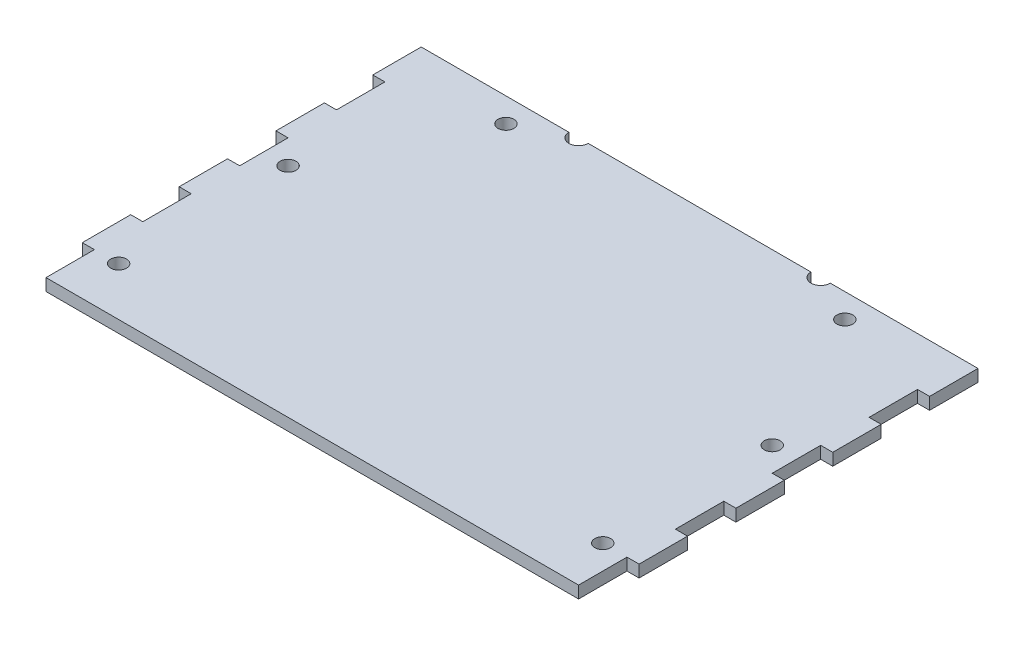
SolidWorks part; units mm, degrees
ref_plane "Front Plane" through (0, 0, 0) normal (0, 0, 1) x (1, 0, 0)
ref_plane "Top Plane" through (0, 0, 0) normal (0, 1, 0) x (1, 0, 0)
ref_plane "Right Plane" through (0, 0, 0) normal (1, 0, 0) x (0, 0, -1)
sketch "Sketch2" plane through (0, 0, 0) normal (0, 1, 0) x (1, 0, 0)
  line L0 (3.175, 0) -> (3.175, 12.7)
  line L1 (3.175, 12.7) -> (0, 12.7)
  line L2 (0, 50.8) -> (0, 38.1)
  line L3 (0, 25.4) -> (3.175, 25.4)
  line L4 (3.175, 38.1) -> (0, 38.1)
  line L5 (0, 76.2) -> (0, 63.5)
  line L6 (0, 50.8) -> (3.175, 50.8)
  line L7 (3.175, 63.5) -> (0, 63.5)
  line L8 (146.05, 101.6) -> (146.05, 88.9)
  line L9 (0, 76.2) -> (3.175, 76.2)
  line L10 (3.175, 25.4) -> (3.175, 38.1)
  line L11 (3.175, 88.9) -> (0, 88.9)
  line L12 (146.05, 25.4) -> (146.05, 12.7)
  line L13 (0, 101.6) -> (3.175, 101.6)
  line L14 (3.175, 50.8) -> (3.175, 63.5)
  line L15 (3.175, 88.9) -> (28.575, 88.9) construction
  line L16 (28.575, 88.9) -> (28.575, 95.25) construction
  line L17 (117.475, 88.9) -> (117.475, 95.25) construction
  line L18 (3.175, 76.2) -> (3.175, 88.9)
  line L19 (9.525, 0) -> (9.525, 12.7) construction
  line L20 (136.525, 0) -> (136.525, 12.7) construction
  line L21 (3.175, 101.6) -> (38.735, 101.6)
  line L22 (142.875, 88.9) -> (117.475, 88.9) construction
  line L23 (73.025, 101.6) -> (73.025, 0) construction
  line L24 (142.875, 57.15) -> (136.525, 57.15) construction
  line L25 (0, 101.6) -> (0, 88.9)
  line L26 (0, 25.4) -> (0, 12.7)
  line L27 (146.05, 50.8) -> (146.05, 38.1)
  line L28 (146.05, 76.2) -> (146.05, 63.5)
  line L29 (43.815, 101.6) -> (102.235, 101.6)
  line L30 (142.875, 76.2) -> (142.875, 88.9)
  line L31 (107.315, 101.6) -> (142.875, 101.6)
  line L34 (142.875, 50.8) -> (142.875, 63.5)
  line L35 (146.05, 101.6) -> (142.875, 101.6)
  line L37 (142.875, 88.9) -> (146.05, 88.9)
  line L38 (142.875, 25.4) -> (142.875, 38.1)
  line L39 (146.05, 76.2) -> (142.875, 76.2)
  line L41 (142.875, 63.5) -> (146.05, 63.5)
  line L42 (146.05, 50.8) -> (142.875, 50.8)
  line L44 (142.875, 38.1) -> (146.05, 38.1)
  line L45 (146.05, 25.4) -> (142.875, 25.4)
  line L47 (142.875, 12.7) -> (146.05, 12.7)
  line L48 (142.875, 0) -> (142.875, 12.7)
  line L49 (142.875, 0) -> (3.175, 0)
  line L52 (3.175, 57.15) -> (9.525, 57.15) construction
  line L54 (-3.175, 152.4) -> (3.175, 152.4) [skipped]
  line L56 (3.175, 139.7) -> (-3.175, 139.7) [skipped]
  line L58 (3.175, 114.3) -> (-3.175, 114.3) [skipped]
  line L60 (-3.175, 127) -> (3.175, 127) [skipped]
  circle A0 centre (136.525, 57.15) radius 2.0828
  circle A1 centre (9.525, 12.7) radius 2.0828
  circle A2 centre (9.525, 57.15) radius 2.0828
  circle A3 centre (136.525, 12.7) radius 2.0828
  circle A4 centre (28.575, 95.25) radius 2.0828
  circle A5 centre (117.475, 95.25) radius 2.0828
  arc A6 (38.735, 101.6) -> (43.815, 101.6) centre (41.275, 101.6) ccw
  arc A7 (107.315, 101.6) -> (102.235, 101.6) centre (104.775, 101.6) cw
  dimension "D1" = 6
  dimension "D3" = 6.35
  dimension "D2" = 25.4
  dimension "D5" = 38.1
  dimension "D4" = 12.7
extrude "Boss-Extrude1" add sketch "Sketch2" along normal blind 3.175
